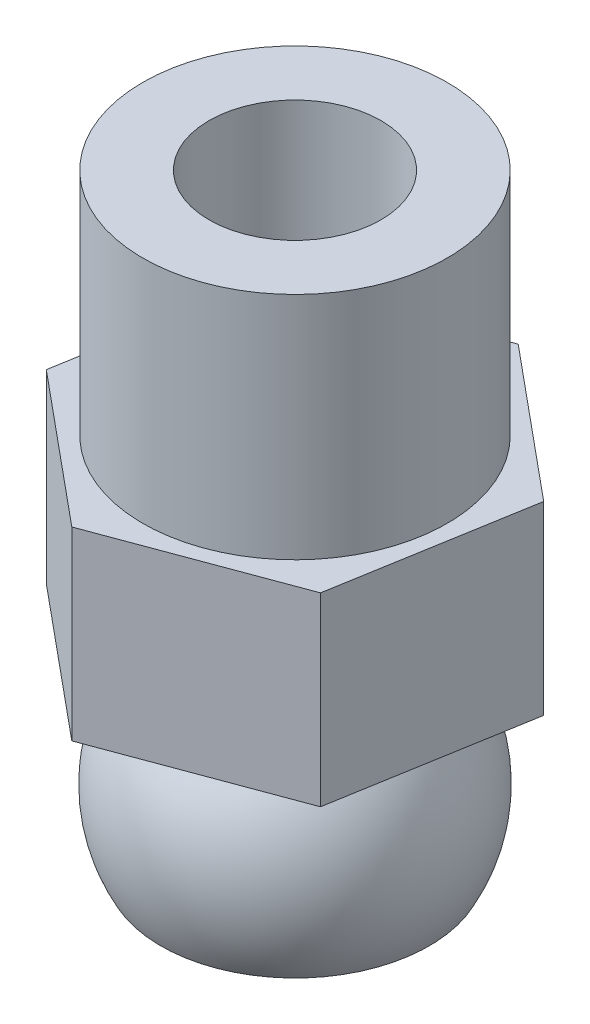
SolidWorks part; units mm, degrees
ref_plane "Alzado" through (0, 0, 0) normal (0, 0, 1) x (1, 0, 0)
ref_plane "Planta" through (0, 0, 0) normal (0, 1, 0) x (1, 0, 0)
ref_plane "Vista lateral" through (0, 0, 0) normal (1, 0, 0) x (0, 0, -1)
sketch "Croquis1" plane through (0, 0, 0) normal (0, 0, 1) x (1, 0, 0)
  line L0 (7.8137, 3.9562) -> (7.8137, -20.36)
  line L1 (7.8137, -5.2838) -> (1.6937, -5.2838)
  line L2 (0.0337, -5.2838) -> (1.6937, -5.2838)
  line L3 (1.6937, -5.2838) -> (1.6937, 3.9562)
  line L4 (1.6937, 3.9562) -> (7.8137, 3.9562)
  line L5 (3.465, -13.06) -> (3.465, -12.7338)
  line L6 (4.3558, -20.36) -> (4.3558, 3.9562)
  line L9 (3.465, -13.06) -> (7.8137, -17.4087)
  line L11 (3.465, -13.06) -> (3.465, -20.36)
  line L12 (0.96, -20.36) -> (7.8137, -20.36)
  line L15 (3.9096, -19.5442) -> (4.3558, -20.36)
  line L18 (7.8137, -12.7338) -> (0.0337, -12.7338)
  line L19 (1.7, 0) -> (1.7, -2.84) construction
  line L20 (1.7, -2.84) -> (5.165, -11.43) construction
  line L21 (0.0337, -12.7338) -> (0.0337, -5.2838)
  line L23 (5.165, -11.43) -> (5.165, -13.8328) construction
  line L24 (0, -3.17) -> (3.465, -11.76) construction
  line L25 (3.465, -11.76) -> (3.465, -13.06) construction
  line L26 (0, 0) -> (0, -3.17) construction
  arc A0 (3.465, -13.06) -> (2.4181, -20.36) centre (7.8137, -17.4087) ccw
  arc A2 (5.165, -13.8328) -> (3.9096, -19.5442) centre (7.8137, -17.4087) ccw
  dimension "D1" = 1.7
revolve "Revolución1" add sketch "Croquis1" angle 360 about L0
sketch "Croquis2" plane through (0, -5.2838, 0) normal (0, 1, 0) x (-1, 0, 0)
  line L1 (-13.8037, 4.9647) -> (-15.1083, -2.7051)
  line L2 (-15.1083, -2.7051) -> (-9.1183, -7.6698)
  line L3 (-9.1183, -7.6698) -> (-1.8237, -4.9647)
  line L4 (-1.8237, -4.9647) -> (-0.5191, 2.7051)
  line L5 (-0.5191, 2.7051) -> (-6.5091, 7.6698)
  line L6 (-6.5091, 7.6698) -> (-13.8037, 4.9647)
  circle A0 centre (-7.8137, 0) radius 6.7377 construction
  circle A1 centre (-7.8137, 0) radius 7.78
  circle M1 centre (-7.8137, 0) radius 7.78
extrude "Cortar-Extruir1" cut sketch "Croquis2" against normal up to next contours L6 M1 | L1 M1 | L2 M1 | L3 M1 | L4 M1 | L5 M1
